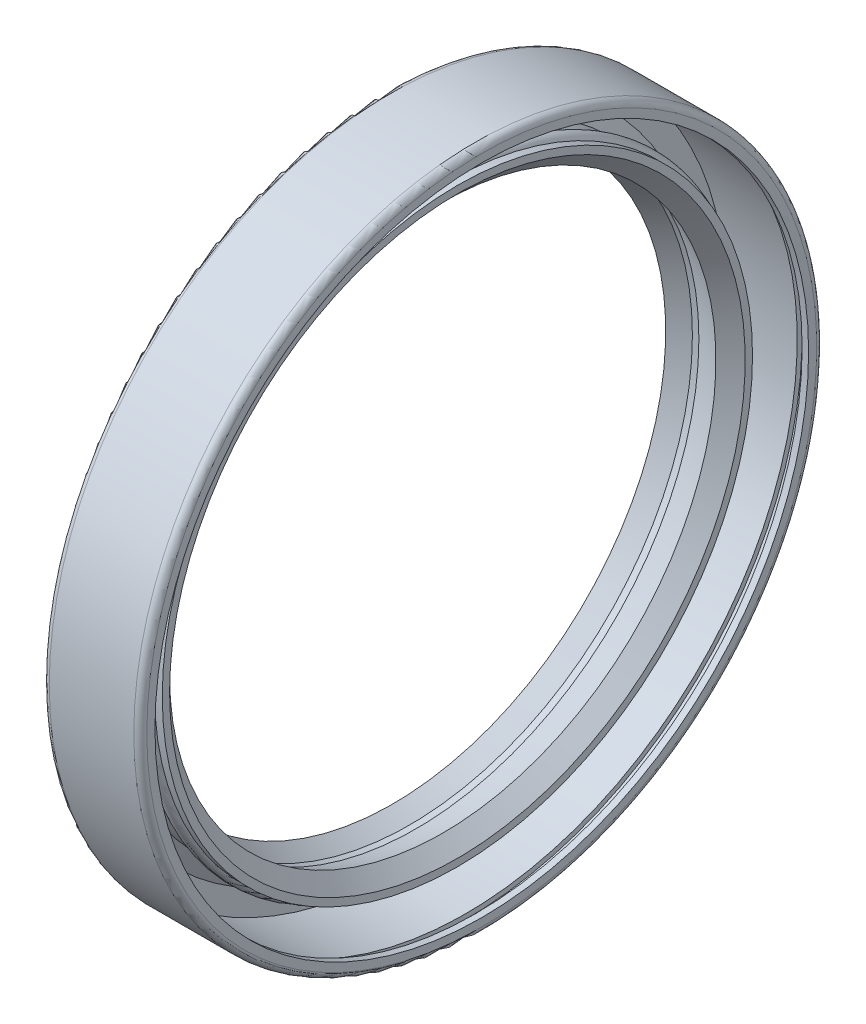
SolidWorks part; units mm, degrees
ref_plane "Plan1" through (0, 0, 0) normal (0, 0, 1) x (1, 0, 0)
ref_plane "Plan2" through (0, 0, 0) normal (0, 1, 0) x (1, 0, 0)
ref_plane "Plan3" through (0, 0, 0) normal (1, 0, 0) x (0, 0, -1)
sketch "Esquisse1" plane through (0, 0, 0) normal (0, 1, 0) x (1, 0, 0)
  line L0 (0, 0) -> (4.1667, 0) construction
  line L1 (0, 15.683) -> (0, 17.1667)
  line L2 (0.3333, 17.5) -> (4.6667, 17.5)
  line L3 (4.1667, 17) -> (4.1667, 17.25)
  line L4 (4.1667, 17) -> (0.5, 17)
  line L5 (0.5, 17) -> (0.5, 15.817)
  line L6 (0, 15.683) -> (0.25, 15.25)
  line L7 (0.25, 15.25) -> (0, 15.25)
  line L8 (0, 15.25) -> (0, 14.8333)
  line L9 (4.1667, 17.25) -> (4.6667, 17.25)
  line L10 (1.6263, 14.5) -> (1.2936, 14.5)
  line L11 (4.6667, 17.25) -> (4.6667, 16.75)
  line L12 (5, 16.75) -> (5, 17.1667)
  line L13 (4.6667, 16.75) -> (5, 16.75)
  line L14 (1.6263, 14.5) -> (3, 14)
  line L15 (3, 14) -> (3.75, 14.75)
  line L16 (3.75, 14.75) -> (3.75, 15.125)
  line L17 (3.75, 15.125) -> (3.3536, 15.125)
  line L18 (0.5, 15.817) -> (0.9717, 15)
  line L19 (1.2936, 14.5) -> (0.4276, 14)
  line L20 (0.4276, 14) -> (0.25, 14.3075)
  line L21 (0.25, 14.3075) -> (0.5833, 14.5)
  line L22 (0.9717, 15) -> (2.625, 15)
  line L23 (0.5833, 14.5) -> (0.3333, 14.5)
  arc A0 (0, 17.1667) -> (0.3333, 17.5) centre (0.3333, 17.1667) cw
  arc A1 (3.3536, 15.125) -> (2.625, 15) centre (3, 15) ccw
  arc A2 (4.6667, 17.5) -> (5, 17.1667) centre (4.6667, 17.1667) cw
  arc A3 (0, 14.8333) -> (0.3333, 14.5) centre (0.3333, 14.8333) ccw
  point P13 (0, 17.5)
  point P22 (5, 17.5)
  dimension "D1" = 120
  dimension "De" = 17.5
  dimension "b" = 5
  dimension "D7" = 45
  dimension "D6" = 20
  dimension "Di" = 14
  dimension "pl" = 3.75
  dimension "D16" = 60
  dimension "h" = 0.125
revolve "Base-Révolution" add sketch "Esquisse1" angle 360 about L0
equation "\"e@Esquisse1\" = \"b@Esquisse1\"/10"
equation "\"i@Esquisse1\"=\"e@Esquisse1\"/2"
equation "\"r@Esquisse1\"=\"e@Esquisse1\"*2/3"
equation "\"l@Esquisse1\"=\"i@Esquisse1\"*3"
equation "\"pl@Esquisse1\"=\"b@Esquisse1\"*3/4"
equation "\"h@Esquisse1\"=\"i@Esquisse1\"/2"
